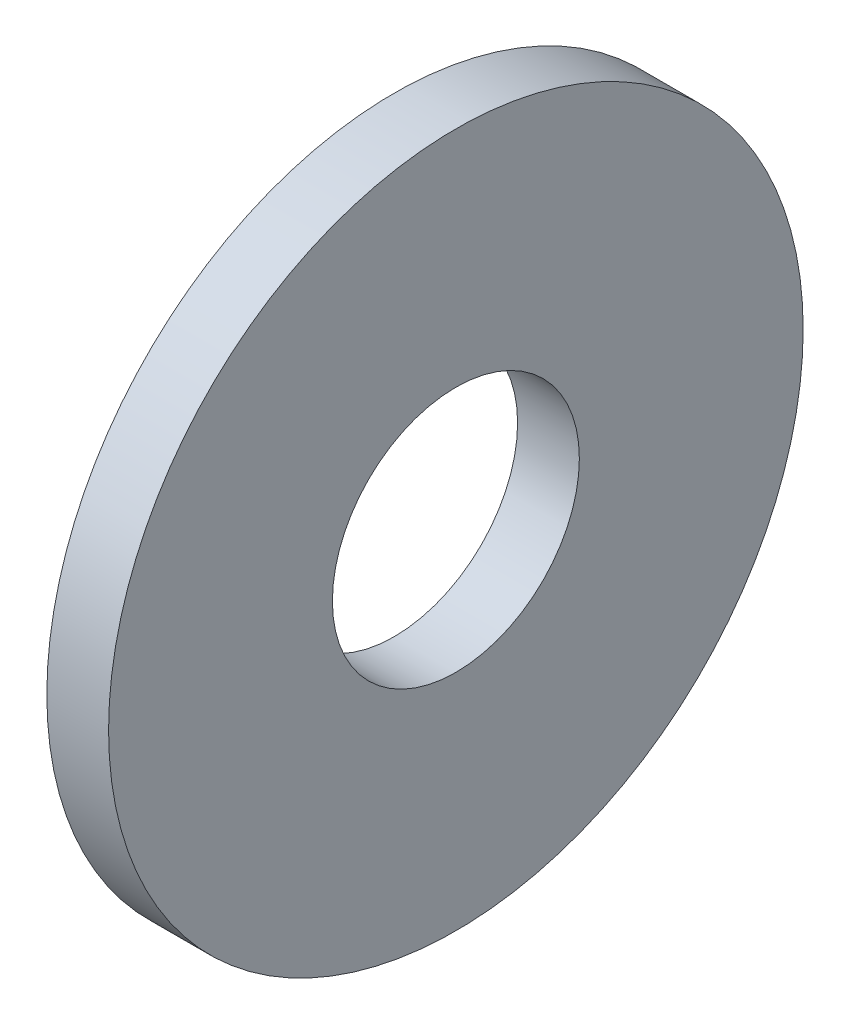
SolidWorks part; units mm, degrees
ref_plane "Plane1" through (0, 0, 0) normal (0, 0, 1) x (1, 0, 0)
ref_plane "Plane2" through (0, 0, 0) normal (0, 1, 0) x (1, 0, 0)
ref_plane "Plane3" through (0, 0, 0) normal (1, 0, 0) x (0, 0, -1)
revolve "Base-Revolve" add sketch "Sketch1" angle 360 about L0
sketch "Sketch1" plane through (0, 0, 0) normal (0, 0, 1) x (1, 0, 0)
  line L0 (-34.925, 0) -> (9.525, 0) construction
  line L1 (0, 3.2) -> (0, 9)
  line L2 (0, 9) -> (-1.6, 9)
  line L3 (-1.6, 9) -> (-1.6, 3.2)
  line L4 (-1.6, 3.2) -> (0, 3.2)
  dimension "Thickness" = 1.6
  dimension "Inside_dia" = 6.4
  dimension "Outside_dia" = 18
